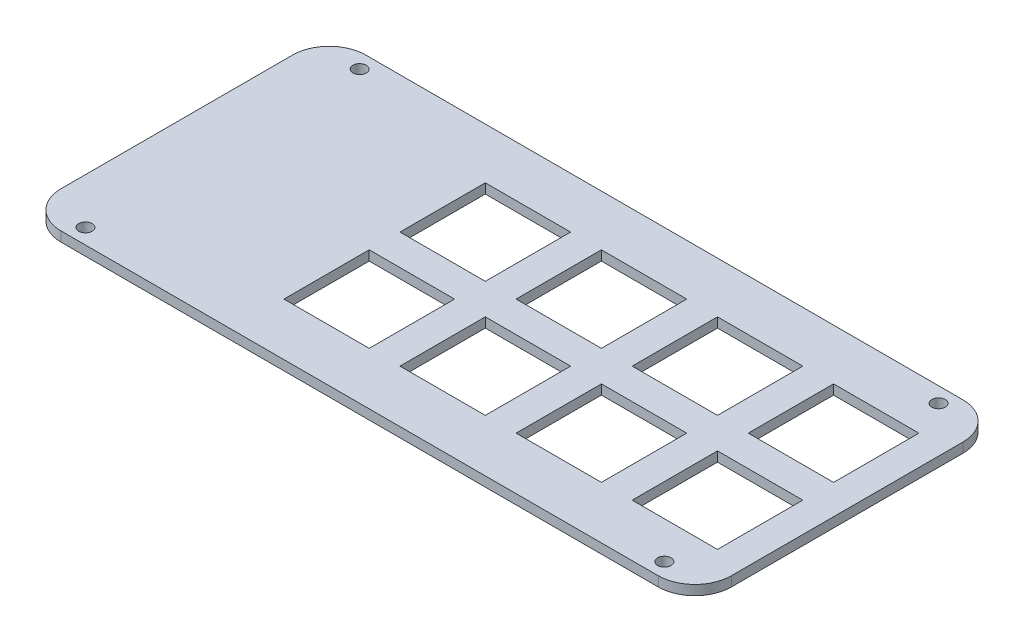
SolidWorks part; units mm, degrees
ref_plane "Ebene vorne" through (0, 0, 0) normal (0, 0, 1) x (1, 0, 0)
ref_plane "Ebene oben" through (0, 0, 0) normal (0, 1, 0) x (1, 0, 0)
ref_plane "Ebene rechts" through (0, 0, 0) normal (1, 0, 0) x (0, 0, -1)
sketch "Skizze1" plane through (0, 0, 0) normal (0, 1, 0) x (1, 0, 0)
  line L13 (-49, 25) -> (49, 25)
  line L14 (-55, 19) -> (-55, -19)
  line L15 (-49, -25) -> (49, -25)
  line L16 (55, 19) -> (55, -19)
  line L17 (-55, 25) -> (55, -25) construction
  line L18 (-55, -25) -> (55, 25) construction
  circle A0 centre (47.5, 22.5) radius 1.1
  circle A1 centre (-47.5, 22.5) radius 1.1
  circle A2 centre (47.5, -22.5) radius 1.1
  circle A3 centre (-47.5, -22.5) radius 1.1
  arc A4 (49, 25) -> (55, 19) centre (49, 19) cw
  arc A5 (49, -25) -> (55, -19) centre (49, -19) ccw
  arc A6 (-55, -19) -> (-49, -25) centre (-49, -19) ccw
  arc A7 (-49, 25) -> (-55, 19) centre (-49, 19) ccw
  point P0 (0, 0)
  point P12 (-47.5, -14.8211)
  point P13 (-30.3529, 28.848)
  point P17 (0, 0)
  dimension "D8" = 2.2
  dimension "D1" = 6
  dimension "D3" = 7.5
  dimension "D4" = 110
  dimension "D5" = 50
  dimension "D6" = 7.5
  dimension "D7" = 2.5
  dimension "D9" = 2.5
extrude "Aufsatz-Linear austragen1" add sketch "Skizze1" along normal blind 1.6
sketch "Skizze2" plane through (0, 1.6, 0) normal (0, 1, 0) x (1, 0, 0)
  line L0 (55, -19) -> (55, 19) construction
  line L1 (36.12, 16.65) -> (50.12, 16.65)
  line L2 (36.12, 16.65) -> (36.12, 2.65)
  line L3 (36.12, 2.65) -> (50.12, 2.65)
  line L4 (50.12, 16.65) -> (50.12, 2.65)
  line L5 (49, 25) -> (-49, 25) construction
  line L6 (36.12, -2.4) -> (36.12, -16.4)
  line L7 (36.12, -2.4) -> (50.12, -2.4)
  line L8 (50.12, -2.4) -> (50.12, -16.4)
  line L9 (36.12, -16.4) -> (50.12, -16.4)
  line L10 (17.07, -2.4) -> (17.07, -16.4)
  line L11 (17.07, -2.4) -> (31.07, -2.4)
  line L12 (31.07, -2.4) -> (31.07, -16.4)
  line L13 (17.07, -16.4) -> (31.07, -16.4)
  line L14 (-1.98, -2.4) -> (-1.98, -16.4)
  line L15 (-1.98, -2.4) -> (12.02, -2.4)
  line L16 (12.02, -2.4) -> (12.02, -16.4)
  line L17 (-1.98, -16.4) -> (12.02, -16.4)
  line L18 (-21.03, -2.4) -> (-21.03, -16.4)
  line L19 (-21.03, -2.4) -> (-7.03, -2.4)
  line L20 (-7.03, -2.4) -> (-7.03, -16.4)
  line L21 (-21.03, -16.4) -> (-7.03, -16.4)
  line L22 (17.07, 16.65) -> (17.07, 2.65)
  line L23 (17.07, 16.65) -> (31.07, 16.65)
  line L24 (31.07, 16.65) -> (31.07, 2.65)
  line L25 (17.07, 2.65) -> (31.07, 2.65)
  line L26 (-1.98, 16.65) -> (-1.98, 2.65)
  line L27 (-1.98, 16.65) -> (12.02, 16.65)
  line L28 (12.02, 16.65) -> (12.02, 2.65)
  line L29 (-1.98, 2.65) -> (12.02, 2.65)
  line L30 (-21.03, 16.65) -> (-21.03, 2.65)
  line L31 (-21.03, 16.65) -> (-7.03, 16.65)
  line L32 (-7.03, 16.65) -> (-7.03, 2.65)
  line L33 (-21.03, 2.65) -> (-7.03, 2.65)
  point P4 (43.12, 16.65)
  point P7 (36.12, 9.65)
  dimension "D1" = 14
  dimension "D2" = 11.88
  dimension "D3" = 15.35
  dimension "D4" = 2
  dimension "D5" = 4
extrude "Schnitt-Linear austragen1" cut sketch "Skizze2" against normal through all
